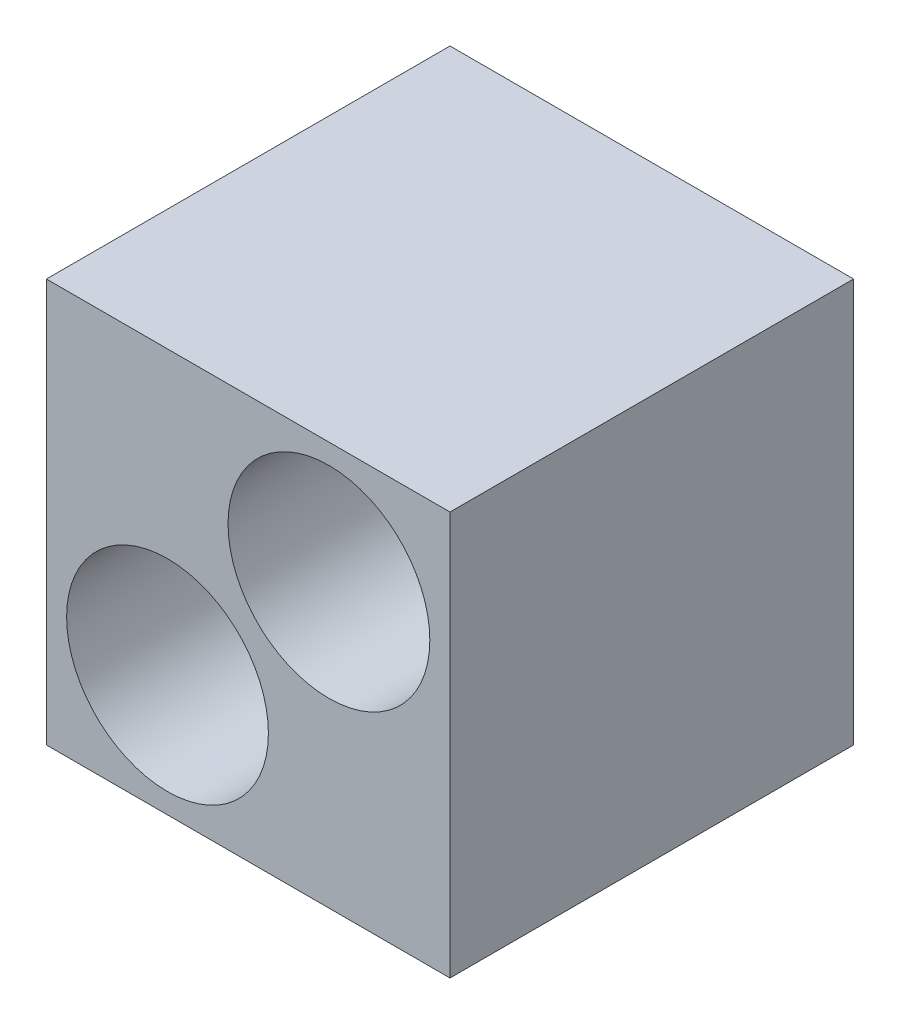
SolidWorks part; units mm, degrees
ref_plane "Front Plane" through (0, 0, 0) normal (0, 0, 1) x (1, 0, 0)
ref_plane "Top Plane" through (0, 0, 0) normal (0, 1, 0) x (1, 0, 0)
ref_plane "Right Plane" through (0, 0, 0) normal (1, 0, 0) x (0, 0, -1)
sketch "Sketch1" plane through (0, 0, 0) normal (0, 0, 1) x (1, 0, 0)
  line L1 (0, 0) -> (10, 0)
  line L2 (0, 0) -> (0, 10)
  line L3 (0, 10) -> (10, 10)
  line L4 (10, 0) -> (10, 10)
extrude "Boss-Extrude1" add sketch "Sketch1" along normal blind 10
sketch "Sketch2" plane through (0, 0, 10) normal (0, 0, 1) x (1, 0, 0)
  circle A0 centre (3, 3) radius 2.5
extrude "Cut-Extrude1" cut sketch "Sketch2" against normal through all
sketch "Sketch3" plane through (0, 0, 10) normal (0, 0, 1) x (1, 0, 0)
  circle A0 centre (7, 7) radius 2.5
extrude "Cut-Extrude2" cut sketch "Sketch3" against normal through all
